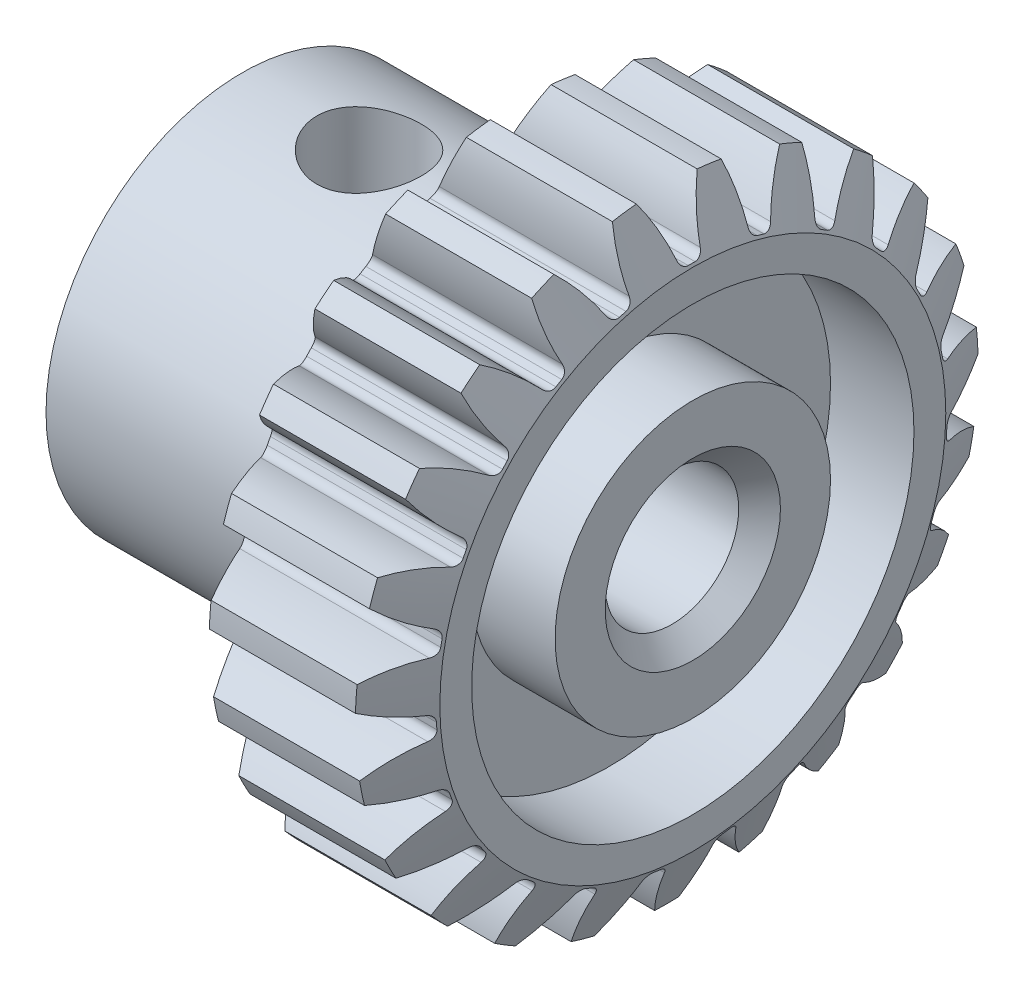
SolidWorks part; units mm, degrees
ref_plane "Front Plane" through (0, 0, 0) normal (0, 0, 1) x (1, 0, 0)
ref_plane "Top Plane" through (0, 0, 0) normal (0, 1, 0) x (1, 0, 0)
ref_plane "Right Plane" through (0, 0, 0) normal (1, 0, 0) x (0, 0, -1)
sketch "Sketch1" plane through (0, 0, 0) normal (0, 0, 1) x (1, 0, 0)
  line L0 (5.4, 0) -> (-5.4, 0) construction
  line L1 (-5.4, 0) -> (-5.4, 4.7)
  line L2 (-5.4, 4.7) -> (0.65, 4.7)
  line L3 (0.65, 4.7) -> (0.65, 7.5)
  line L4 (0.65, 7.5) -> (5.4, 7.5)
  line L5 (5.4, 7.5) -> (5.4, 5.3)
  line L6 (5.4, 5.3) -> (3.4, 5.3)
  line L7 (3.4, 5.3) -> (3.4, 3.3)
  line L8 (3.4, 3.3) -> (5.4, 3.3)
  line L9 (5.4, 3.3) -> (5.4, 0)
  line L10 (-5.4, 0) -> (5.4, 0)
  dimension "D1" = 4.7
  dimension "D2" = 7.5
  dimension "D3" = 3.3
  dimension "D4" = 2.2
  dimension "D5" = 10.8
  dimension "D6" = 4.75
  dimension "D7" = 2
revolve "Revolve1" add sketch "Sketch1" angle 360 about L0
sketch "Sketch2" plane through (5.4, 0, 0) normal (1, 0, 0) x (0, 0, -1)
  circle A0 centre (0, 0) radius 1.6
  dimension "D1" = 3.2
extrude "Cut-Extrude1" cut sketch "Sketch2" against normal through all
chamfer "Chamfer1" distance 0.5 angle 45 2 edges at (5.4, 0, -1.6) (-5.4, 0, -1.6)
hole_wizard "M3x0.5 Tapped Hole1" positions "3DSketch4" profile "Sketch8" tap size "M3x0.5" standard "ANSI Metric"
sketch3d "3DSketch4"
  point P0 (-2.3583, 4.7, 0)
sketch "Sketch8" plane through (-2.3583, 4.7, 0) normal (1, 0, 0) x (0, 0, 1)
  line L0 (0, 0) -> (0, 4.7511)
  line L1 (0, 4.7511) -> (1.25, 4)
  line L2 (1.25, 4) -> (1.25, 0)
  line L5 (1.25, 0) -> (0, 0)
  line L10 (0, 4.7511) -> (-1.25, 4) construction
  line L11 (0, -6.35) -> (0, 107.95) construction
  dimension "Tap Drill Dia." = 2.5
  dimension "Tap Drill Depth" = 4
  dimension "Drill Angle" = 118
cosmetic thread "Hole Thread3" parameters "D1"=3.7013, "D2"=3
sketch "Sketch9" plane through (5.4, 0, 0) normal (1, 0, 0) x (0, 0, -1)
  line L0 (0, 0) -> (0, 8.0721) construction
  arc A0 (0.0812, 6.1245) -> (-0.0812, 6.1245) centre (0, 0) ccw
  arc A1 (0.8265, 7.5801) -> (-0.8265, 7.5801) centre (0, 0) ccw
  circle A2 centre (0, 0) radius 7.5 construction
  arc A3 (0.0812, 6.1245) -> (0.2798, 6.2843) centre (0.0838, 6.3244) ccw
  arc A5 (-0.8265, 7.5801) -> (-0.2798, 6.2843) centre (-3.8, 5.5621) cw
  arc A6 (0.8265, 7.5801) -> (0.2798, 6.2843) centre (3.8, 5.5621) ccw
  arc A7 (-0.2798, 6.2843) -> (-0.0812, 6.1245) centre (-0.0838, 6.3244) ccw
  point P4 (0.25, 6.1199)
  point P6 (0.75, 7.4624)
  dimension "D1" = 15.25
  dimension "D2" = 12.25
  dimension "D3" = 0.25
  dimension "D6" = 0.2
  dimension "D4" = 0.75
  dimension "D5" = 3.8
extrude "Cut-Extrude3" cut sketch "Sketch9" against normal up to next
ref_axis "Axis1" through (-4.9, 0, 0) along (1, 0, 0)
pattern_circular "CirPattern1" count 23 over 360 about axis through (0, 0, 0) along (1, 0, 0) of "Cut-Extrude3"
sketch "Sketch10" plane through (0, 0, 0) normal (0, 0, 1) x (1, 0, 0)
  line L0 (5.4, 6.0624) -> (4.775, 7.4624)
  line L1 (5.4, 7.4624) -> (0.65, 7.4624) construction
  line L2 (4.775, 7.4624) -> (1.275, 7.4624)
  line L3 (1.275, 7.4624) -> (0.65, 6.0624)
  line L4 (0.65, 6.0624) -> (-0.6351, 6.6361)
  line L5 (-0.6351, 6.6361) -> (0.1802, 8.4624)
  line L6 (5.8698, 8.4624) -> (6.6851, 6.6361)
  line L7 (6.6851, 6.6361) -> (5.4, 6.0624)
  line L8 (3.025, 6.9833) -> (3.025, 7.8636) construction
  line L9 (5.4, 6.9833) -> (0.65, 6.9833) construction
  line L10 (0.1802, 8.4624) -> (5.8698, 8.4624)
  line L11 (5.4, 5.5147) -> (5.4, 6.7657) construction
  line L12 (0.65, 6.7657) -> (0.65, 5.5147) construction
  point P15 (3.025, 7.4624)
  dimension "D1" = 1.4
  dimension "D2" = 3.5
  dimension "D3" = 1
  dimension "D4" = 2
revolve "Cut-Revolve1" cut sketch "Sketch10" angle 360 about axis through (-4.9, 0, 0) along (1, 0, 0)
